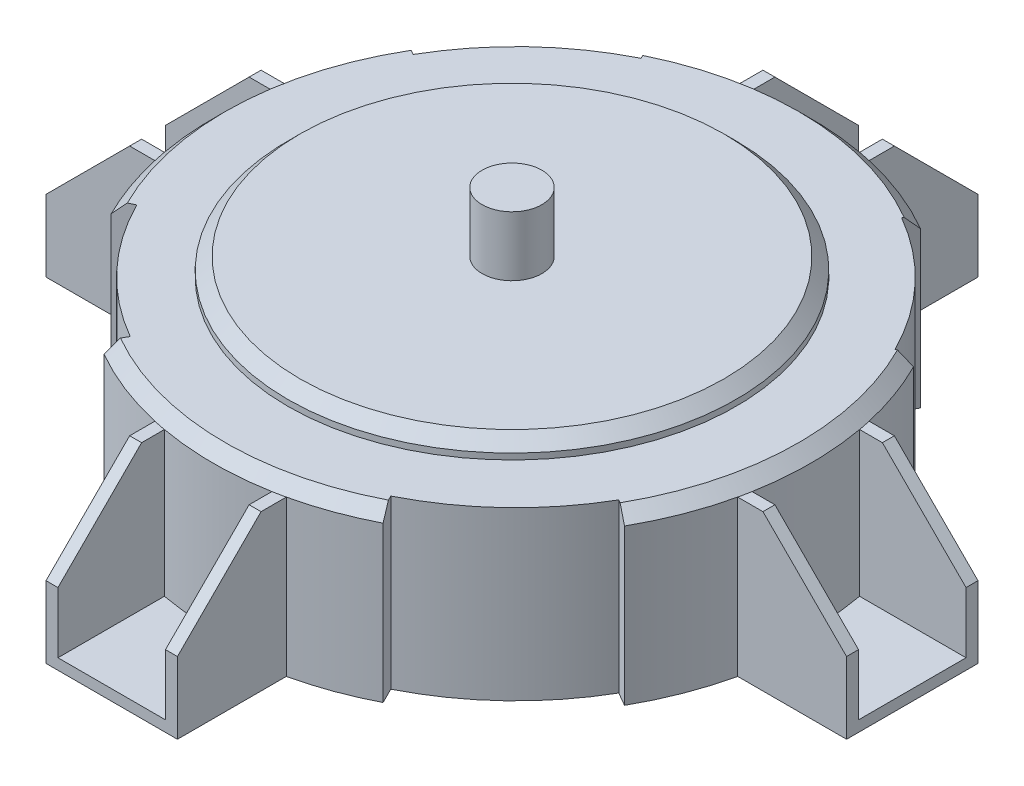
SolidWorks part; units mm, degrees
ref_plane "Front Plane" through (0, 0, 0) normal (0, 0, 1) x (1, 0, 0)
ref_plane "Top Plane" through (0, 0, 0) normal (0, 1, 0) x (1, 0, 0)
ref_plane "Right Plane" through (0, 0, 0) normal (1, 0, 0) x (0, 0, -1)
sketch "Sketch1" plane through (0, 0, 0) normal (0, 1, 0) x (1, 0, 0)
  circle A0 centre (0, 0) radius 50
  dimension "D1" = 100
extrude "Boss-Extrude1" add sketch "Sketch1" along normal blind 28
sketch "Sketch2" plane through (0, 28, 0) normal (0, 1, 0) x (1, 0, 0)
  circle A0 centre (0, 0) radius 37.5
  dimension "D1" = 75
extrude "Boss-Extrude2" add sketch "Sketch2" along normal blind 3
chamfer "Chamfer1" distance 2 angle 45 2 edges at (0, 28, 50) (0, 31, 37.5)
sketch "Sketch3" plane through (0, 31, 0) normal (0, 1, 0) x (1, 0, 0)
  circle A0 centre (0, 0) radius 5
  dimension "D1" = 10
extrude "Boss-Extrude3" add sketch "Sketch3" along normal blind 10
sketch "Sketch4" plane through (0, 0, 0) normal (0, 0, 1) x (1, 0, 0)
  line L0 (-50, 26) -> (50, 26) construction
  line L1 (-8.9983, 1.8231) -> (8.9983, 1.8231)
  line L2 (-8.9983, 1.8231) -> (-8.9983, 26)
  line L4 (8.9983, 1.8231) -> (8.9983, 26)
  line L5 (-10.9983, 0) -> (10.9983, 0)
  line L6 (8.9983, 26) -> (10.9983, 26)
  line L7 (-10.9983, 26) -> (-8.9983, 26)
  line L8 (-10.9983, 26) -> (-10.9983, 0)
  line L9 (-50, 0) -> (50, 0) construction
  line L11 (10.9983, 26) -> (10.9983, 0)
  point P0 (0, 13.9115)
extrude "Boss-Extrude4" add sketch "Sketch4" against normal blind 67
pattern_circular "CirPattern6" count 4 over 360 about axis through (0, 0, 0) along (0, 1, 0) of "Boss-Extrude4"
chamfer "Chamfer2" distance 14 angle 45 8 edges at (9.9983, 26, -67) (-9.9983, 26, -67) (-67, 26, -9.9983) (-9.9983, 26, 67) (-67, 26, 9.9983) (67, 26, 9.9983) (67, 26, -9.9983) (9.9983, 26, 67)
sketch "Sketch10" plane through (0, 0, 0) normal (0, -1, 0) x (-1, 0, 0)
  line L0 (24.9319, -43.3405) -> (23.3363, -40.5667)
  line L1 (44.7211, -22.3613) -> (41.8589, -20.9302)
  arc A0 (10.9983, -48.7754) -> (48.7754, -10.9983) centre (0, 0) ccw construction
  arc A1 (23.3363, -40.5667) -> (41.8589, -20.9302) centre (0, 0) ccw
  arc A2 (24.9319, -43.3405) -> (44.7211, -22.3613) centre (0, 0) ccw
extrude "Cut-Extrude1" cut sketch "Sketch10" against normal blind 67
pattern_circular "CirPattern7" count 4 every 90 about axis through (0.3385, 0, -0.3193) along (0, 1, 0) of "Cut-Extrude1"
ref_plane "Plane1" through (0, -10, 0) normal (0, -1, 0) x (-1, 0, 0)
